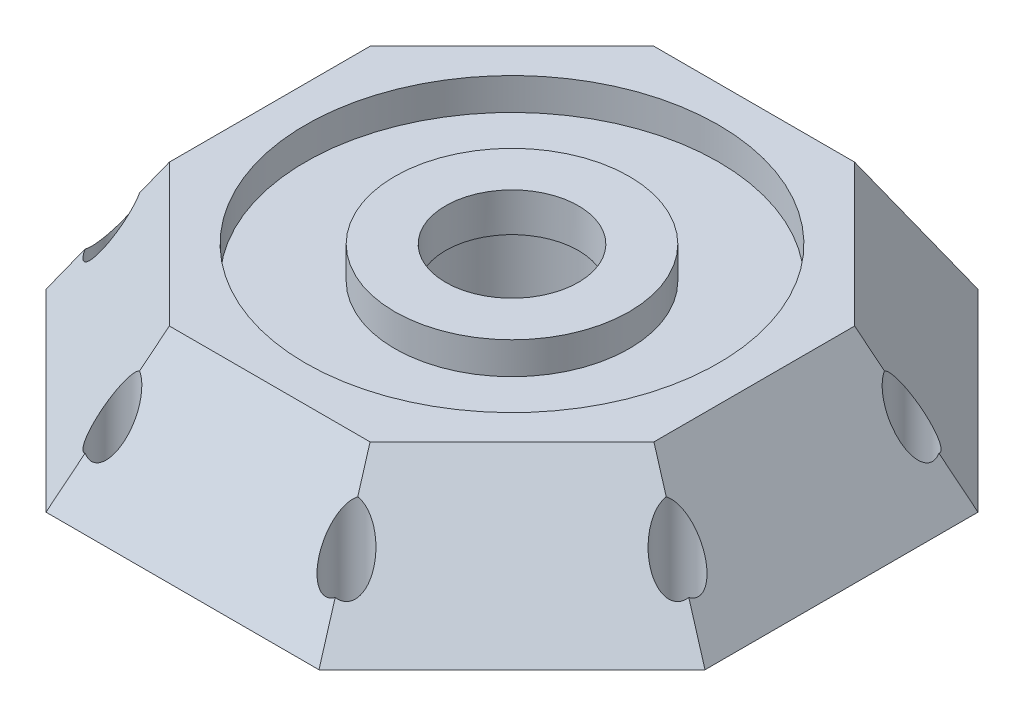
SolidWorks part; units mm, degrees
ref_plane "前视基准面" through (0, 0, 0) normal (0, 0, 1) x (1, 0, 0)
ref_plane "上视基准面" through (0, 0, 0) normal (0, 1, 0) x (1, 0, 0)
ref_plane "右视基准面" through (0, 0, 0) normal (1, 0, 0) x (0, 0, -1)
sketch "草图1" plane through (0, 0, 0) normal (0, 1, 0) x (1, 0, 0)
  line L9 (34, -14.0833) -> (34, 14.0833)
  line L10 (34, 14.0833) -> (14.0833, 34)
  line L11 (14.0833, 34) -> (-14.0833, 34)
  line L12 (-14.0833, 34) -> (-34, 14.0833)
  line L13 (-34, 14.0833) -> (-34, -14.0833)
  line L14 (-34, -14.0833) -> (-14.0833, -34)
  line L15 (-14.0833, -34) -> (14.0833, -34)
  line L16 (14.0833, -34) -> (34, -14.0833)
  circle A0 centre (0, 0) radius 34 construction
  dimension "D1" = 68
ref_plane "基准面1" through (0, 14, 0) normal (0, 1, 0) x (1, 0, 0)
sketch "草图3" plane through (0, 14, 0) normal (0, 1, 0) x (1, 0, 0)
  line L1 (25, 10.3553) -> (10.3553, 25)
  line L2 (10.3553, 25) -> (-10.3553, 25)
  line L3 (-10.3553, 25) -> (-25, 10.3553)
  line L4 (-25, 10.3553) -> (-25, -10.3553)
  line L5 (-25, -10.3553) -> (-10.3553, -25)
  line L6 (-10.3553, -25) -> (10.3553, -25)
  line L7 (10.3553, -25) -> (25, -10.3553)
  line L8 (25, -10.3553) -> (25, 10.3553)
  circle A0 centre (0, 0) radius 25 construction
  dimension "D1" = 50
loft "放样1" add profiles "草图3", "草图1"
sketch "草图4" plane through (0, 14, 0) normal (0, 1, 0) x (1, 0, 0)
  line L0 (-25, 10.3553) -> (-34, 14.0833) construction
  circle A0 centre (0, 0) radius 6.85
  circle A9 centre (-29.1575, 12.0774) radius 2.15
  circle A10 centre (-12.0774, 29.1575) radius 2.15 [skipped]
  circle A11 centre (12.0774, 29.1575) radius 2.15 [skipped]
  circle A12 centre (29.1575, 12.0774) radius 2.15
  circle A13 centre (29.1575, -12.0774) radius 2.15
  circle A14 centre (12.0774, -29.1575) radius 2.15
  circle A15 centre (-12.0774, -29.1575) radius 2.15
  circle A16 centre (-29.1575, -12.0774) radius 2.15
  point P23 (0, 0)
  point P26 (0, 0)
  dimension "D1" = 13.7
  dimension "D2" = 4.3
  dimension "D3" = 4.5
  dimension "D4" = 8
extrude "切除-拉伸1" cut sketch "草图4" against normal through all
sketch "草图5" plane through (0, 14, 0) normal (0, 1, 0) x (1, 0, 0)
  line L64 (-25, 10.3553) -> (-27.1711, 11.2546) construction
  line L65 (-26.8614, 9.7813) -> (-25.9103, 12.0774)
  line L66 (-25.9103, 12.0774) -> (-26.8614, 14.3735)
  line L67 (-26.8614, 14.3735) -> (-29.1575, 15.3246)
  line L68 (-29.1575, 15.3246) -> (-31.4536, 14.3735)
  line L69 (-31.4536, 14.3735) -> (-32.4046, 12.0774)
  line L70 (-32.4046, 12.0774) -> (-31.4536, 9.7813)
  line L71 (-31.4536, 9.7813) -> (-29.1575, 8.8302)
  line L72 (-29.1575, 8.8302) -> (-26.8614, 9.7813)
  line L73 (-12.0774, 25.9103) -> (-9.7813, 26.8614) [skipped]
  line L74 (-9.7813, 26.8614) -> (-8.8302, 29.1575) [skipped]
  line L75 (-8.8302, 29.1575) -> (-9.7813, 31.4536) [skipped]
  line L76 (-9.7813, 31.4536) -> (-12.0774, 32.4046) [skipped]
  line L77 (-12.0774, 32.4046) -> (-14.3735, 31.4536) [skipped]
  line L78 (-14.3735, 31.4536) -> (-15.3246, 29.1575) [skipped]
  line L79 (-15.3246, 29.1575) -> (-14.3735, 26.8614) [skipped]
  line L80 (-14.3735, 26.8614) -> (-12.0774, 25.9103) [skipped]
  line L81 (9.7813, 26.8614) -> (12.0774, 25.9103) [skipped]
  line L82 (12.0774, 25.9103) -> (14.3735, 26.8614) [skipped]
  line L83 (14.3735, 26.8614) -> (15.3246, 29.1575) [skipped]
  line L84 (15.3246, 29.1575) -> (14.3735, 31.4536) [skipped]
  line L85 (14.3735, 31.4536) -> (12.0774, 32.4046) [skipped]
  line L86 (12.0774, 32.4046) -> (9.7813, 31.4536) [skipped]
  line L87 (9.7813, 31.4536) -> (8.8302, 29.1575) [skipped]
  line L88 (8.8302, 29.1575) -> (9.7813, 26.8614) [skipped]
  line L89 (25.9103, 12.0774) -> (26.8614, 9.7813)
  line L90 (26.8614, 9.7813) -> (29.1575, 8.8302)
  line L91 (29.1575, 8.8302) -> (31.4536, 9.7813)
  line L92 (31.4536, 9.7813) -> (32.4046, 12.0774)
  line L93 (32.4046, 12.0774) -> (31.4536, 14.3735)
  line L94 (31.4536, 14.3735) -> (29.1575, 15.3246)
  line L95 (29.1575, 15.3246) -> (26.8614, 14.3735)
  line L96 (26.8614, 14.3735) -> (25.9103, 12.0774)
  line L97 (26.8614, -9.7813) -> (25.9103, -12.0774)
  line L98 (25.9103, -12.0774) -> (26.8614, -14.3735)
  line L99 (26.8614, -14.3735) -> (29.1575, -15.3246)
  line L100 (29.1575, -15.3246) -> (31.4536, -14.3735)
  line L101 (31.4536, -14.3735) -> (32.4046, -12.0774)
  line L102 (32.4046, -12.0774) -> (31.4536, -9.7813)
  line L103 (31.4536, -9.7813) -> (29.1575, -8.8302)
  line L104 (29.1575, -8.8302) -> (26.8614, -9.7813)
  line L105 (12.0774, -25.9103) -> (9.7813, -26.8614)
  line L106 (9.7813, -26.8614) -> (8.8302, -29.1575)
  line L107 (8.8302, -29.1575) -> (9.7813, -31.4536)
  line L108 (9.7813, -31.4536) -> (12.0774, -32.4046)
  line L109 (12.0774, -32.4046) -> (14.3735, -31.4536)
  line L110 (14.3735, -31.4536) -> (15.3246, -29.1575)
  line L111 (15.3246, -29.1575) -> (14.3735, -26.8614)
  line L112 (14.3735, -26.8614) -> (12.0774, -25.9103)
  line L113 (-9.7813, -26.8614) -> (-12.0774, -25.9103)
  line L114 (-12.0774, -25.9103) -> (-14.3735, -26.8614)
  line L115 (-14.3735, -26.8614) -> (-15.3246, -29.1575)
  line L116 (-15.3246, -29.1575) -> (-14.3735, -31.4536)
  line L117 (-14.3735, -31.4536) -> (-12.0774, -32.4046)
  line L118 (-12.0774, -32.4046) -> (-9.7813, -31.4536)
  line L119 (-9.7813, -31.4536) -> (-8.8302, -29.1575)
  line L120 (-8.8302, -29.1575) -> (-9.7813, -26.8614)
  line L121 (-25.9103, -12.0774) -> (-26.8614, -9.7813)
  line L122 (-26.8614, -9.7813) -> (-29.1575, -8.8302)
  line L123 (-29.1575, -8.8302) -> (-31.4536, -9.7813)
  line L124 (-31.4536, -9.7813) -> (-32.4046, -12.0774)
  line L125 (-32.4046, -12.0774) -> (-31.4536, -14.3735)
  line L126 (-31.4536, -14.3735) -> (-29.1575, -15.3246)
  line L127 (-29.1575, -15.3246) -> (-26.8614, -14.3735)
  line L128 (-26.8614, -14.3735) -> (-25.9103, -12.0774)
  circle A0 centre (-29.1575, 12.0774) radius 3 construction
  point P72 (0, 0)
  dimension "D1" = 6
  dimension "D2" = 4.5
  dimension "D3" = 8
sketch "草图6" plane through (0, 14, 0) normal (0, 1, 0) x (1, 0, 0)
  circle A0 centre (0, 0) radius 12.1
  circle A1 centre (0, 0) radius 21.3
  dimension "D1" = 42.6
  dimension "D2" = 24.2
extrude "切除-拉伸3" cut sketch "草图6" against normal blind 3.3
sketch "草图7" plane through (0, 0, 0) normal (0, -1, 0) x (1, 0, 0)
  circle A0 centre (0, 0) radius 7.85
  dimension "D1" = 15.7
extrude "切除-拉伸4" cut sketch "草图7" against normal blind 10
